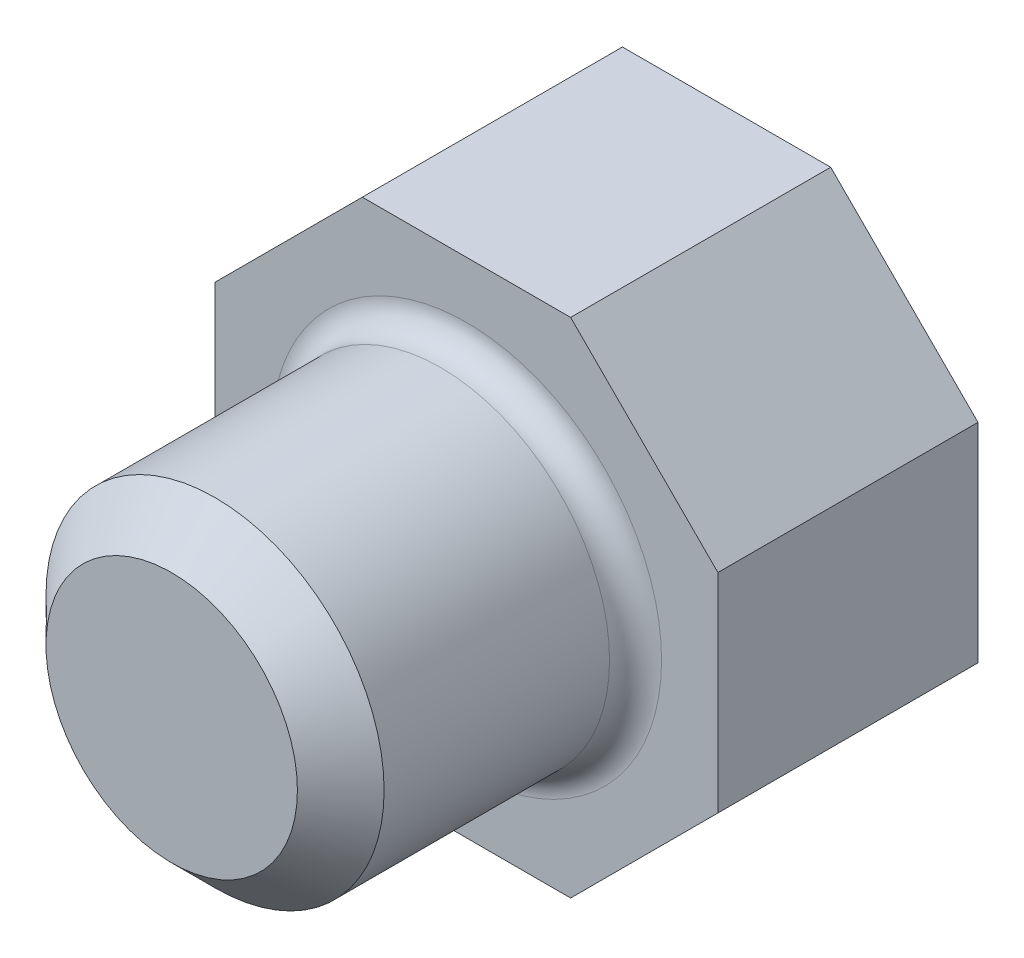
SolidWorks part; units mm, degrees
ref_plane "Alzado" through (0, 0, 0) normal (1, 0, 0) x (0, 1, 0)
ref_plane "Planta" through (0, 0, 0) normal (0, 0, 1) x (0, 1, 0)
ref_plane "Vista lateral" through (0, 0, 0) normal (0, 1, 0) x (-1, 0, 0)
sketch "Croquis1" plane through (0, 0, 0) normal (0, 0, 1) x (0, 1, 0)
  line L0 (0, 0) -> (3.7723, 0) construction
  line L1 (5.8, -2.4024) -> (5.8, 2.4024)
  line L2 (5.8, 2.4024) -> (2.4024, 5.8)
  line L3 (2.4024, 5.8) -> (-2.4024, 5.8)
  line L4 (-2.4024, 5.8) -> (-5.8, 2.4024)
  line L5 (-5.8, 2.4024) -> (-5.8, -2.4024)
  line L6 (-5.8, -2.4024) -> (-2.4024, -5.8)
  line L7 (-2.4024, -5.8) -> (2.4024, -5.8)
  line L8 (2.4024, -5.8) -> (5.8, -2.4024)
  circle A0 centre (0, 0) radius 5.8 construction
  dimension "D1" = 11.6
extrude "Saliente-Extruir1" add sketch "Croquis1" along normal blind 6
sketch "Croquis2" plane through (0, 0, 6) normal (0, 0, 1) x (1, 0, 0)
  circle A0 centre (0, 0) radius 3.9
  dimension "D1" = 7.8
extrude "Saliente-Extruir2" add sketch "Croquis2" along normal blind 6.8
chamfer "Chaflán1" distance 1 angle 45 1 edges at (3.9, 0, 12.8)
fillet "Redondeo1" radius 0.6 1 edges at (3.9, 0, 6)
